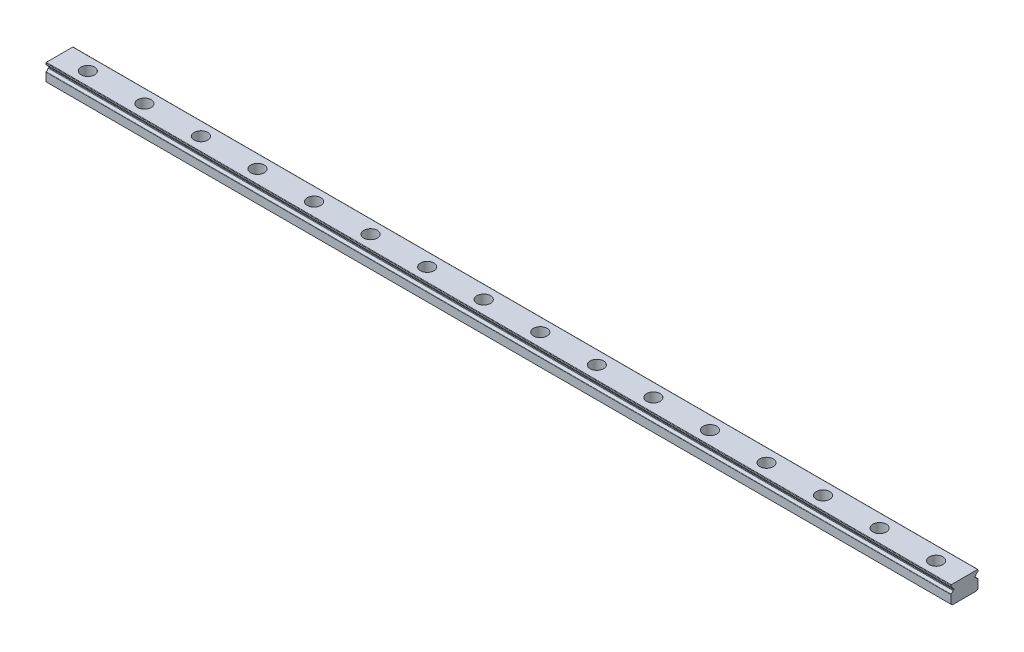
SolidWorks part; units mm, degrees
ref_plane "前视基准面" through (0, 0, 0) normal (0, 0, 1) x (1, 0, 0)
ref_plane "上视基准面" through (0, 0, 0) normal (0, 1, 0) x (1, 0, 0)
ref_plane "右视基准面" through (0, 0, 0) normal (1, 0, 0) x (0, 0, -1)
other "Configuration Table"
ref_plane "基准面1" through (0, 4, 0) normal (0, 1, 0) x (1, 0, 0)
sketch "草图1" plane through (0, 4, 0) normal (0, 1, 0) x (1, 0, 0)
  line L0 (200, -6) -> (200, 6)
  line L1 (200, 6) -> (-200, 6)
  line L2 (-200, 6) -> (-200, -6)
  line L3 (-200, -6) -> (200, -6)
extrude "凸台-拉伸1" add sketch "草图1" against normal blind 8
sketch "草图2" plane through (200, 0, 0) normal (1, 0, 0) x (0, 0, -1)
  line L0 (6, 1.51) -> (6, 2.01)
  line L1 (6, 2.01) -> (4.8, 2.01)
  line L2 (4.8, 1.51) -> (6, 1.51)
  arc A0 (4.8, 2.01) -> (4.8, 1.51) centre (4.8, 1.76) ccw
extrude "切除-拉伸1" cut sketch "草图2" against normal through all
sketch "草图3" plane through (200, 0, 0) normal (1, 0, 0) x (0, 0, -1)
  line L0 (6, 2.01) -> (6, 3.1111)
  line L1 (5.04, 2.01) -> (6, 2.01)
  arc A0 (6, 3.1111) -> (5.04, 2.01) centre (6.4382, 1.76) ccw
extrude "切除-拉伸2" cut sketch "草图3" against normal through all
sketch "草图4" plane through (200, 0, 0) normal (1, 0, 0) x (0, 0, -1)
  line L0 (6, 1.51) -> (5.04, 1.51)
  line L1 (6, 0.4089) -> (6, 1.51)
  arc A0 (5.04, 1.51) -> (6, 0.4089) centre (6.4382, 1.76) ccw
extrude "切除-拉伸3" cut sketch "草图4" against normal through all
sketch "草图5" plane through (200, 0, 0) normal (1, 0, 0) x (0, 0, -1)
  line L0 (-6, 2.01) -> (-6, 1.51)
  line L1 (-6, 1.51) -> (-4.8, 1.51)
  line L2 (-4.8, 2.01) -> (-6, 2.01)
  arc A0 (-4.8, 1.51) -> (-4.8, 2.01) centre (-4.8, 1.76) ccw
extrude "切除-拉伸4" cut sketch "草图5" against normal through all
sketch "草图6" plane through (200, 0, 0) normal (1, 0, 0) x (0, 0, -1)
  line L0 (-6, 1.51) -> (-6, 0.4089)
  line L1 (-5.04, 1.51) -> (-6, 1.51)
  arc A0 (-6, 0.4089) -> (-5.04, 1.51) centre (-6.4382, 1.76) ccw
extrude "切除-拉伸5" cut sketch "草图6" against normal through all
sketch "草图7" plane through (200, 0, 0) normal (1, 0, 0) x (0, 0, -1)
  line L0 (-6, 2.01) -> (-5.04, 2.01)
  line L1 (-6, 3.1111) -> (-6, 2.01)
  arc A0 (-5.04, 2.01) -> (-6, 3.1111) centre (-6.4382, 1.76) ccw
extrude "切除-拉伸6" cut sketch "草图7" against normal through all
hole_wizard "M3 六角头机械螺钉的柱形沉头孔1" positions "草图9" profile "草图8" counterbore size "M3" standard "ANSI Metric"
sketch "草图9" plane through (0, 4, 0) normal (0, 1, 0) x (1, 0, 0)
  point P0 (-187.5, 0)
  point P1 (-162.5, 0)
  point P2 (-137.5, 0)
  point P3 (-112.5, 0)
  point P4 (-87.5, 0)
  point P5 (-62.5, 0)
  point P6 (-37.5, 0)
  point P7 (-12.5, 0)
  point P8 (12.5, 0)
  point P9 (37.5, 0)
  point P10 (62.5, 0)
  point P11 (87.5, 0)
  point P12 (112.5, 0)
  point P13 (137.5, 0)
  point P14 (162.5, 0)
  point P15 (187.5, 0)
sketch "草图8" plane through (-187.5, 4, 0) normal (1, 0, 0) x (0, 0, 1)
  line L0 (0, 0) -> (0, 8)
  line L1 (0, 8) -> (1.75, 8)
  line L3 (1.75, 8) -> (1.75, 4.5)
  line L4 (1.75, 4.5) -> (2.9999, 4.5)
  line L5 (2.9999, 4.5) -> (2.9999, 0)
  line L7 (2.9999, 0) -> (0, 0)
  line L11 (0, -6.35) -> (0, 107.95) construction
  dimension "通孔孔直径" = 3.5
  dimension "通孔孔深度" = 8
  dimension "柱形沉头孔直径" = 5.9999
  dimension "柱形沉头孔深度" = 4.5
chamfer "倒角1" distance 0.6 angle 45 2 edges at (0, -4, -6) (0, -4, 6)
fillet "圆角1" radius 0.2 10 edges at (0, 3.1111, -6) (0, 1.51, -5.04) (0, 4, -6) (0, 1.51, 5.04) (0, 2.01, -5.04) (0, 2.01, 5.04) (0, 4, 6) (0, 3.1111, 6) (0, 0.4089, -6) (0, 0.4089, 6)
